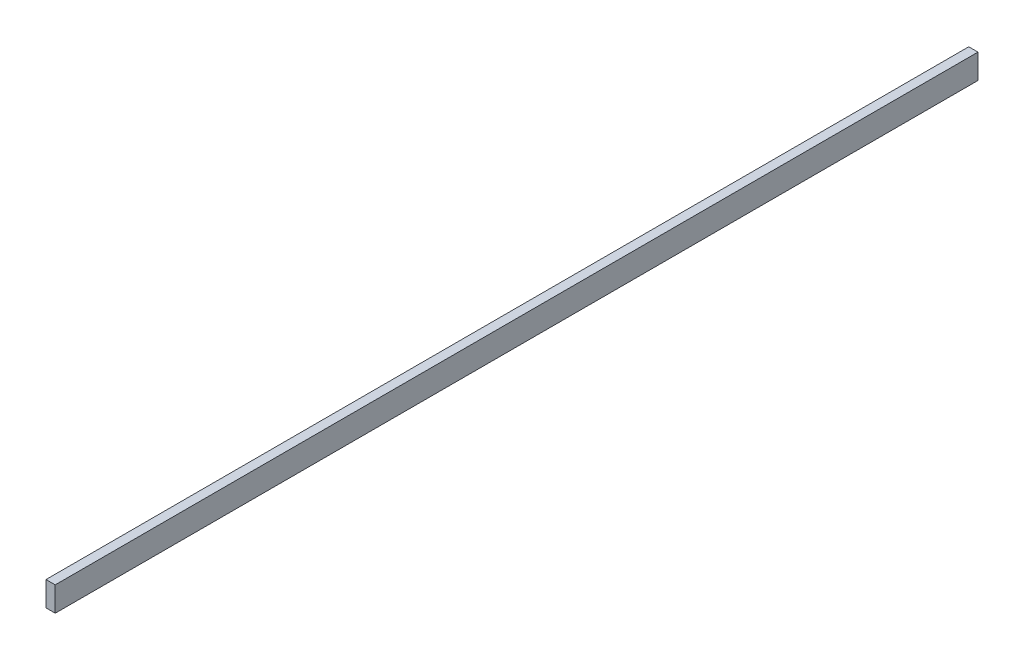
SolidWorks part; units mm, degrees
ref_plane "Front Plane" through (0, 0, 0) normal (0, 0, 1) x (1, 0, 0)
ref_plane "Top Plane" through (0, 0, 0) normal (0, 1, 0) x (1, 0, 0)
ref_plane "Right Plane" through (0, 0, 0) normal (1, 0, 0) x (0, 0, -1)
sketch "Sketch1" plane through (0, 0, 0) normal (0, 0, 1) x (1, 0, 0)
  line L1 (0, 0) -> (75, 0)
  line L2 (0, 0) -> (0, 200)
  line L3 (0, 200) -> (75, 200)
  line L4 (75, 0) -> (75, 200)
  dimension "D1" = 200
  dimension "D2" = 75
extrude "Boss-Extrude1" add sketch "Sketch1" along normal blind 7500
